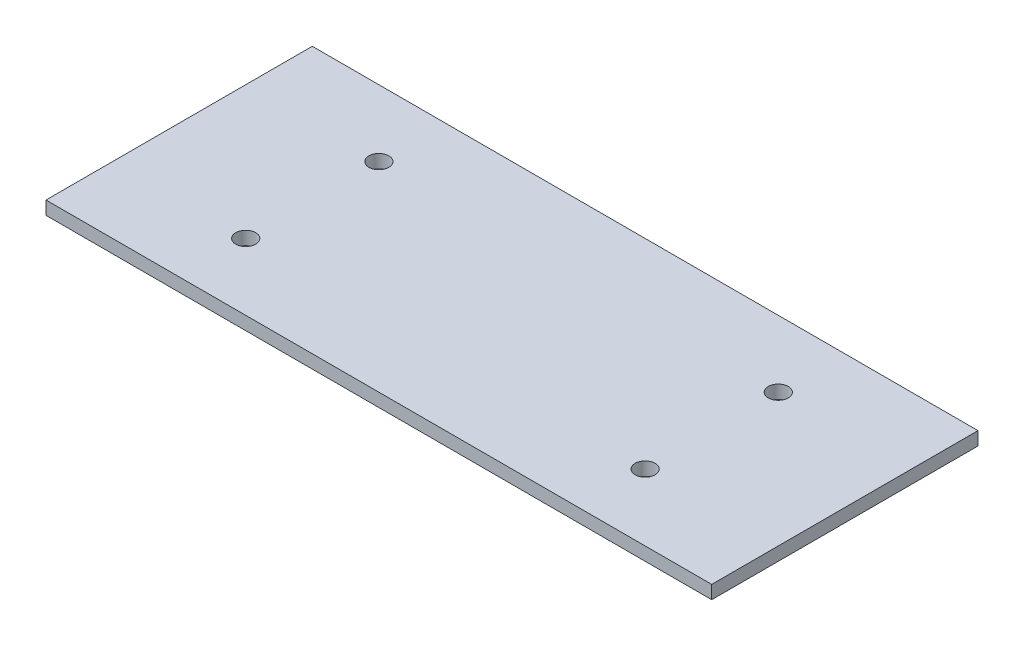
SolidWorks part; units mm, degrees
ref_plane "Front Plane" through (0, 0, 0) normal (0, 0, 1) x (1, 0, 0)
ref_plane "Top Plane" through (0, 0, 0) normal (0, 1, 0) x (1, 0, 0)
ref_plane "Right Plane" through (0, 0, 0) normal (1, 0, 0) x (0, 0, -1)
sketch "Sketch1" plane through (0, 0, 0) normal (0, 1, 0) x (1, 0, 0)
  line L0 (0, 0) -> (100, 0)
  line L1 (100, 0) -> (100, 40)
  line L2 (100, 40) -> (0, 40)
  line L3 (0, 40) -> (0, 0)
  line L4 (50, 20) -> (80, 20)
  line L5 (80, 20) -> (80, 30)
  line L6 (50, 40) -> (50, 25.8089) construction
  line L7 (0, 20) -> (17.1929, 20) construction
  circle A0 centre (80, 30) radius 1.5
  circle A1 centre (20, 30) radius 1.5
  circle A2 centre (80, 10) radius 1.5
  circle A3 centre (20, 10) radius 1.5
  dimension "D5" = 3
  dimension "D1" = 100
  dimension "D2" = 40
  dimension "D3" = 30
  dimension "D4" = 10
extrude "Boss-Extrude1" add sketch "Sketch1" along normal blind 2
